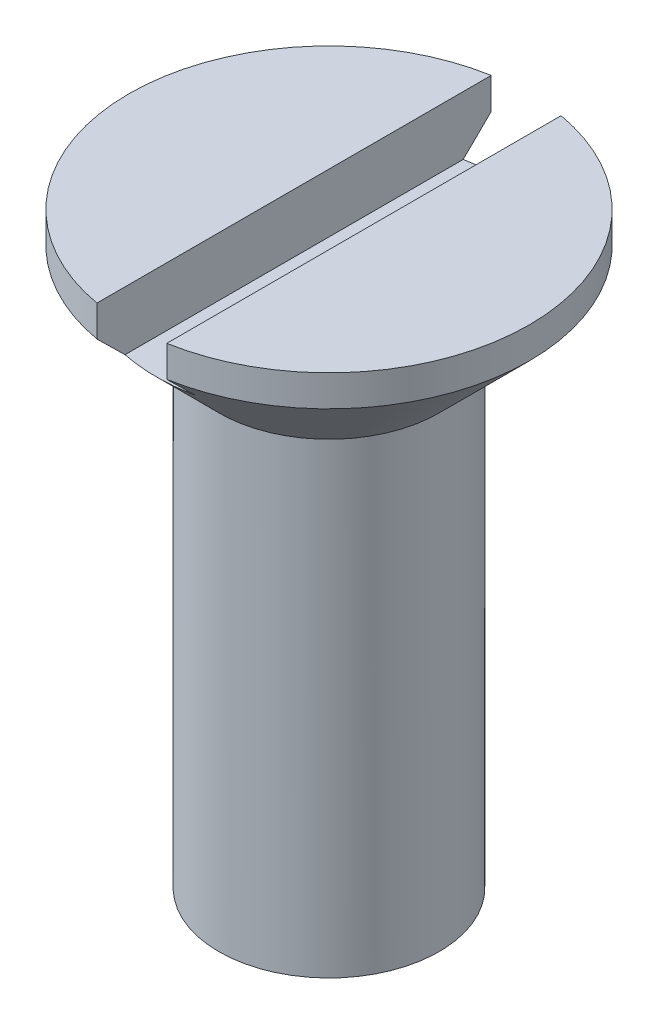
SolidWorks part; units mm, degrees
ref_plane "Front Plane" through (0, 0, 0) normal (0, 0, 1) x (1, 0, 0)
ref_plane "Top Plane" through (0, 0, 0) normal (0, 1, 0) x (1, 0, 0)
ref_plane "Right Plane" through (0, 0, 0) normal (1, 0, 0) x (0, 0, -1)
sketch "Sketch1" plane through (0, 0, 0) normal (0, 0, 1) x (1, 0, 0)
  line L0 (0, 0) -> (0, 50000) construction
  line L1 (0, 17.7321) -> (5.45, 17.7321)
  line L2 (5.45, 17.7321) -> (5.45, 16.8821)
  line L3 (5.45, 16.8821) -> (3, 14.4321)
  line L4 (3, 14.4321) -> (3, 1.7321)
  line L5 (3, 1.7321) -> (0, 0)
  line L6 (0, 0) -> (0, 17.7321)
  dimension "D1" = 45
  dimension "D2" = 3.3
  dimension "D3" = 6
  dimension "D4" = 16
  dimension "D5" = 60
  dimension "D6" = 10.9
revolve "Revolve1" add sketch "Sketch1" angle 360 about L0
sketch "Sketch2" plane through (0, 17.7321, 0) normal (0, 1, 0) x (1, 0, 0)
  line L1 (-0.95, 5.45) -> (0.95, 5.45)
  line L2 (-0.95, 5.45) -> (-0.95, -5.45)
  line L3 (-0.95, -5.45) -> (0.95, -5.45)
  line L4 (0.95, 5.45) -> (0.95, -5.45)
  line L5 (-0.95, 5.45) -> (0.95, -5.45) construction
  line L6 (-0.95, -5.45) -> (0.95, 5.45) construction
  circle A1 centre (0, 0) radius 5.45 construction
  point P0 (0, 0)
  dimension "D1" = 1.9
extrude "Cut-Extrude1" cut sketch "Sketch2" against normal blind 1.6
scale "Scale1" scale about centroid uniform scaling yes scale factor 25.4
scale "Scale2" scale about centroid uniform scaling yes scale factor 0.03937
